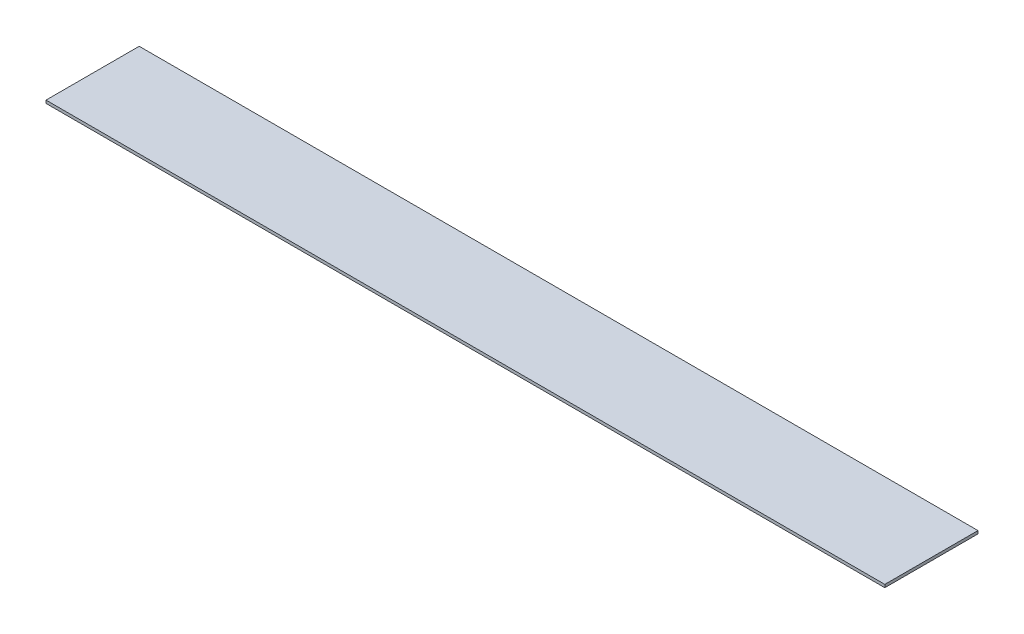
SolidWorks part; units mm, degrees
ref_plane "Front" through (0, 0, 0) normal (0, 0, 1) x (1, 0, 0)
ref_plane "Top" through (0, 0, 0) normal (0, 1, 0) x (1, 0, 0)
ref_plane "Right" through (0, 0, 0) normal (1, 0, 0) x (0, 0, -1)
sketch "Sketch1" plane through (0, 0, 0) normal (0, 1, 0) x (1, 0, 0)
  line L0 (-333.9479, -16.1661) -> (123.2521, -16.1661)
  line L1 (-333.9479, -16.1661) -> (-333.9479, 34.6339)
  line L2 (-333.9479, 34.6339) -> (123.2521, 34.6339)
  line L3 (123.2521, -16.1661) -> (123.2521, 34.6339)
  line L7 (428.0521, 8.4401) -> (428.0521, 10.0276)
  line L10 (123.2521, 10.0276) -> (123.2521, 8.4401) construction
  dimension "D1" = 457.2
  dimension "D2" = 50.8
extrude "Boss-Extrude1" add sketch "Sketch1" along normal blind 1.5875 contours L0 L3 L2 L1
